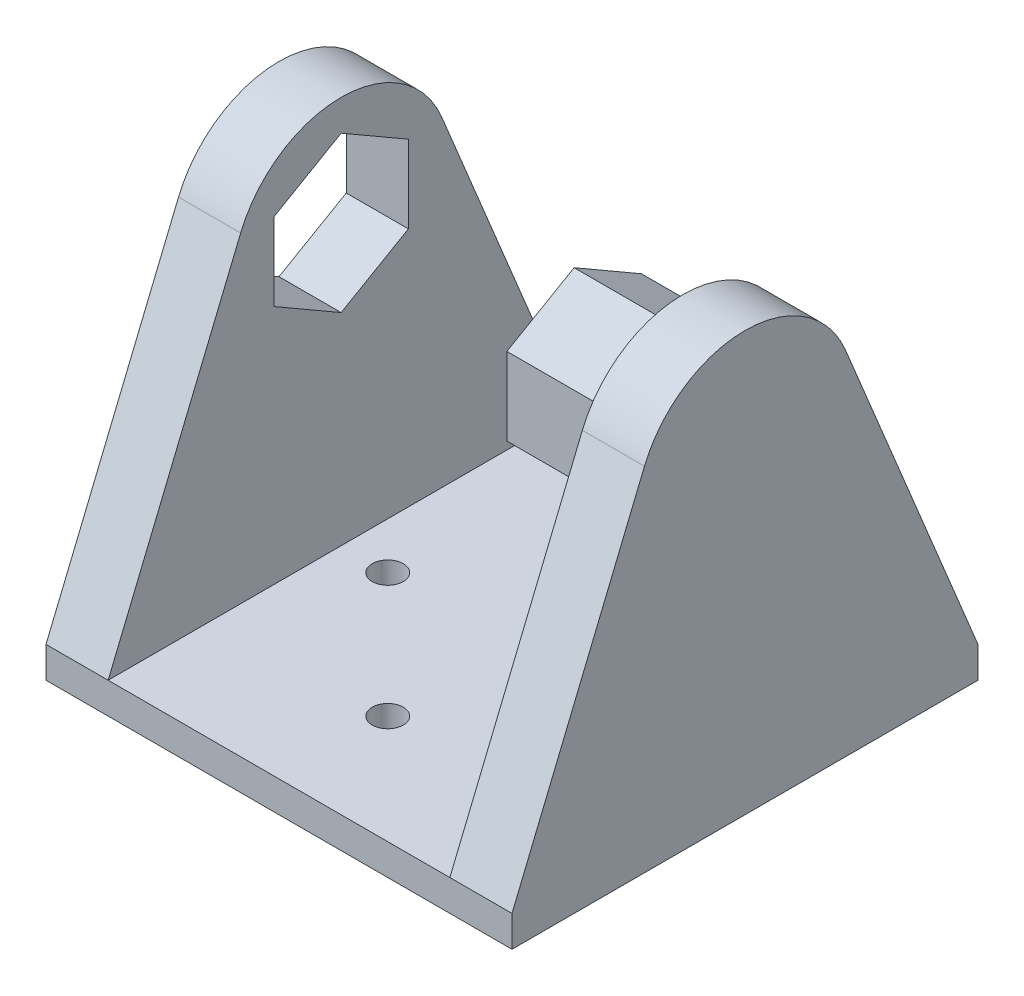
SolidWorks part; units mm, degrees
ref_plane "Front Plane" through (0, 0, 0) normal (0, 0, 1) x (1, 0, 0)
ref_plane "Top Plane" through (0, 0, 0) normal (0, 1, 0) x (1, 0, 0)
ref_plane "Right Plane" through (0, 0, 0) normal (1, 0, 0) x (0, 0, -1)
sketch "Sketch1" plane through (0, 0, 0) normal (0, 1, 0) x (1, 0, 0)
  line L1 (-15, -15) -> (15, -15)
  line L2 (-15, -15) -> (-15, 15)
  line L3 (-15, 15) -> (15, 15)
  line L4 (15, -15) -> (15, 15)
  line L5 (-15, -15) -> (15, 15) construction
  line L6 (-15, 15) -> (15, -15) construction
  point P0 (0, 0)
extrude "Boss-Extrude1" add sketch "Sketch1" along normal blind 2
sketch "Sketch2" plane through (0, 2, 0) normal (0, 1, 0) x (1, 0, 0)
  line L0 (-8, 0) -> (8, 0)
  line L1 (0, -8) -> (0, 8)
  circle A0 centre (0, 8) radius 1
  circle A1 centre (8, 0) radius 1
  circle A2 centre (0, -8) radius 1
  circle A3 centre (-8, 0) radius 1
  point P4 (0, 0)
  point P8 (0, 0)
extrude "Cut-Extrude1" cut sketch "Sketch2" against normal blind 2
sketch "Sketch3" plane through (0, 2, 0) normal (0, 1, 0) x (1, 0, 0)
  line L1 (-15, -15) -> (15, -15) construction
  line L2 (-15, 15) -> (-11, 15)
  line L3 (-15, 15) -> (-15, -15)
  line L4 (-15, -15) -> (-11, -15)
  line L5 (-11, 15) -> (-11, -15)
  line L8 (15, 15) -> (11, 15)
  line L9 (15, 15) -> (15, -15)
  line L10 (15, -15) -> (11, -15)
  line L11 (11, 15) -> (11, -15)
  point P4 (0, 0)
extrude "Boss-Extrude2" add sketch "Sketch3" along normal blind 25
sketch "Sketch5" plane through (-15, 0, 0) normal (-1, 0, 0) x (0, 0, 1)
  line L0 (0, 27) -> (15, 27)
  line L2 (15, 27) -> (15, 0) construction
  line L3 (-15, 0) -> (15, 0)
  line L4 (-15, 0) -> (-15, 2)
  line L6 (15, 0) -> (15, 2)
  line L7 (-15, 2) -> (-6.4708, 22.6701)
  line L8 (15, 2) -> (6.4708, 22.6701)
  line L9 (15, 27) -> (15, 2)
  line L10 (0, 27) -> (-15, 27)
  line L11 (-15, 27) -> (-15, 2)
  arc A0 (6.4708, 22.6701) -> (-6.4708, 22.6701) centre (0, 20) ccw
  line M9 (15, 0) -> (15, 27)
  line M10 (15, 27) -> (-15, 27)
  line M11 (-15, 27) -> (-15, 0)
extrude "Cut-Extrude2" cut sketch "Sketch5" against normal blind 38 contours A0 L8 M9 M10 | A0 L7 M10 M11
sketch "Sketch6" plane through (11, 0, 0) normal (-1, 0, 0) x (0, 0, 1)
  line L1 (0, 25) -> (-4.3301, 22.5)
  line L2 (-4.3301, 22.5) -> (-4.3301, 17.5)
  line L3 (-4.3301, 17.5) -> (0, 15)
  line L4 (0, 15) -> (4.3301, 17.5)
  line L5 (4.3301, 17.5) -> (4.3301, 22.5)
  line L6 (4.3301, 22.5) -> (0, 25)
  circle A0 centre (0, 20) radius 4.3301 construction
  point P0 (0, 20)
extrude "Boss-Extrude3" add sketch "Sketch6" along normal blind 7
sketch "Sketch7" plane through (-15, 0, 0) normal (-1, 0, 0) x (0, 0, 1)
  line L1 (0, 25) -> (-4.3301, 22.5)
  line L2 (-4.3301, 22.5) -> (-4.3301, 17.5)
  line L3 (-4.3301, 17.5) -> (0, 15)
  line L4 (0, 15) -> (4.3301, 17.5)
  line L5 (4.3301, 17.5) -> (4.3301, 22.5)
  line L6 (4.3301, 22.5) -> (0, 25)
  circle A0 centre (0, 20) radius 4.3301 construction
  point P0 (0, 20)
extrude "Cut-Extrude3" cut sketch "Sketch7" against normal blind 7
